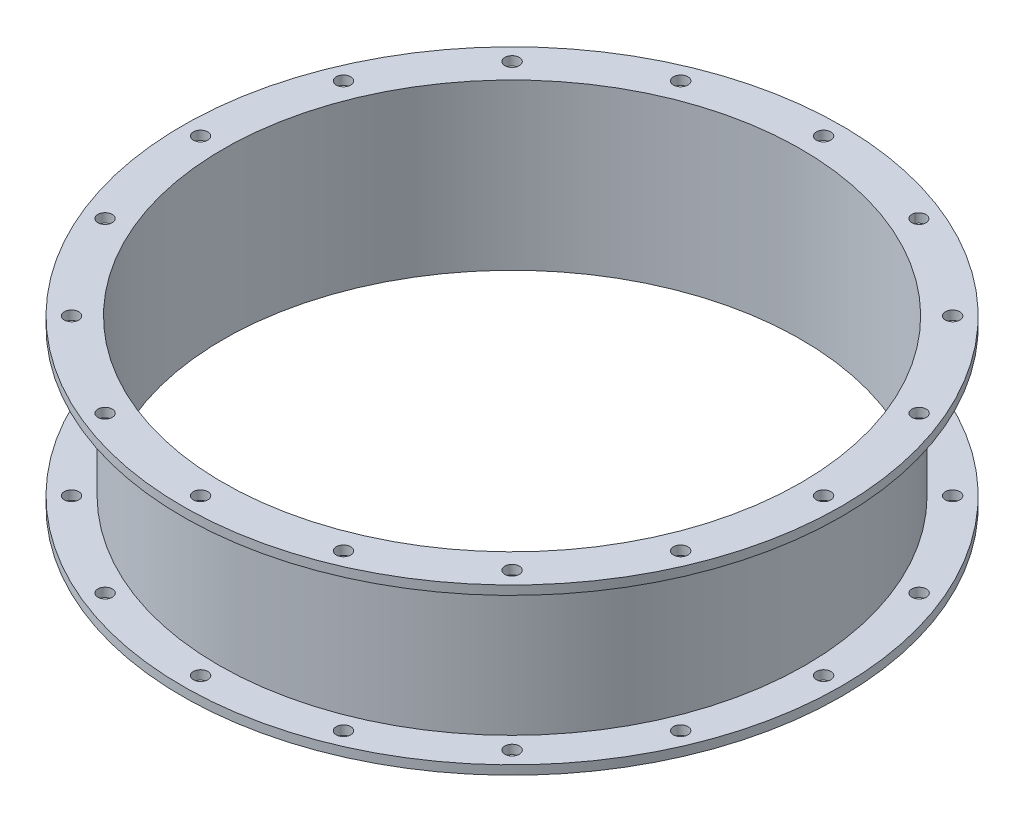
SolidWorks part; units mm, degrees
material "AISI 304"
ref_plane "Front Plane" through (0, 0, 0) normal (0, 0, 1) x (1, 0, 0)
ref_plane "Top Plane" through (0, 0, 0) normal (0, 1, 0) x (1, 0, 0)
ref_plane "Right Plane" through (0, 0, 0) normal (1, 0, 0) x (0, 0, -1)
sketch "Sketch1" plane through (0, 0, 0) normal (0, 0, 1) x (1, 0, 0)
  line L0 (0, -8382.8405) -> (0, 410759.1858) construction
  line L12 (-320, 586.8186) -> (-320, 769.3186)
  line L15 (-325, 759.3186) -> (-325, 596.8186)
  line L16 (-365, 586.8186) -> (-365, 596.8186)
  line L17 (-365, 596.8186) -> (-325, 596.8186)
  line L18 (-365, 586.8186) -> (-320, 586.8186)
  line L19 (-1320, 678.0686) -> (48680, 678.0686) construction
  line L20 (-365, 759.3186) -> (-325, 759.3186)
  line L21 (-365, 769.3186) -> (-365, 759.3186)
  line L23 (-365, 769.3186) -> (-320, 769.3186)
  point P11 (-320, 678.0686)
  dimension "D2" = 640
  dimension "D3" = 10
  dimension "D4" = 45
revolve "Revolve1" add sketch "Sketch1" angle 360 about L0
sketch "Sketch2" plane through (0, 596.8186, 0) normal (0, 1, 0) x (1, 0, 0)
  line L0 (-1000, 0) -> (49000, 0) construction
  line L1 (0, -1000) -> (0, 49000) construction
  line L2 (-452.6973, -187.5134) -> (45741.2793, 18946.6582) construction
  line L3 (-452.6973, 187.5134) -> (45741.2793, -18946.6582) construction
  line L4 (0, 0) -> (19134.1716, 46193.9766) construction
  line L5 (0, 0) -> (-19134.1716, 46193.9766) construction
  line L6 (-707.1068, -707.1068) -> (34648.2323, 34648.2323) construction
  line L7 (707.1068, -707.1068) -> (-34648.2323, 34648.2323) construction
  circle A0 centre (0, 345) radius 8
  circle A1 centre (131.8905, 318.4118) radius 8
  circle A4 centre (132.0258, 318.7384) radius 8
  circle A5 centre (243.9518, 243.9518) radius 8
  circle A6 centre (318.7384, 132.0258) radius 8
  circle A7 centre (345, 0) radius 8
  circle A8 centre (318.7384, -132.0258) radius 8
  circle A9 centre (243.9518, -243.9518) radius 8
  circle A10 centre (132.0258, -318.7384) radius 8
  circle A11 centre (0, -345) radius 8
  circle A12 centre (-132.0258, -318.7384) radius 8
  circle A13 centre (-243.9518, -243.9518) radius 8
  circle A14 centre (-318.7384, -132.0258) radius 8
  circle A15 centre (-345, 0) radius 8
  circle A16 centre (-318.7384, 132.0258) radius 8
  circle A17 centre (-243.9518, 243.9518) radius 8
  circle A18 centre (-132.0258, 318.7384) radius 8
  point P55 (0, 0)
  dimension "D1" = 16
  dimension "D2" = 16
  dimension "D3" = 345
  dimension "D4" = 16
extrude "Cut-Extrude1" cut sketch "Sketch2" against normal through all both and the other way through all contours A12 | A13 | A5 | A1 A4 | A0 | A18 | A17 | A16 | A15 | A11 | A14 | A10 | A9 | A8 | A7 | A6
